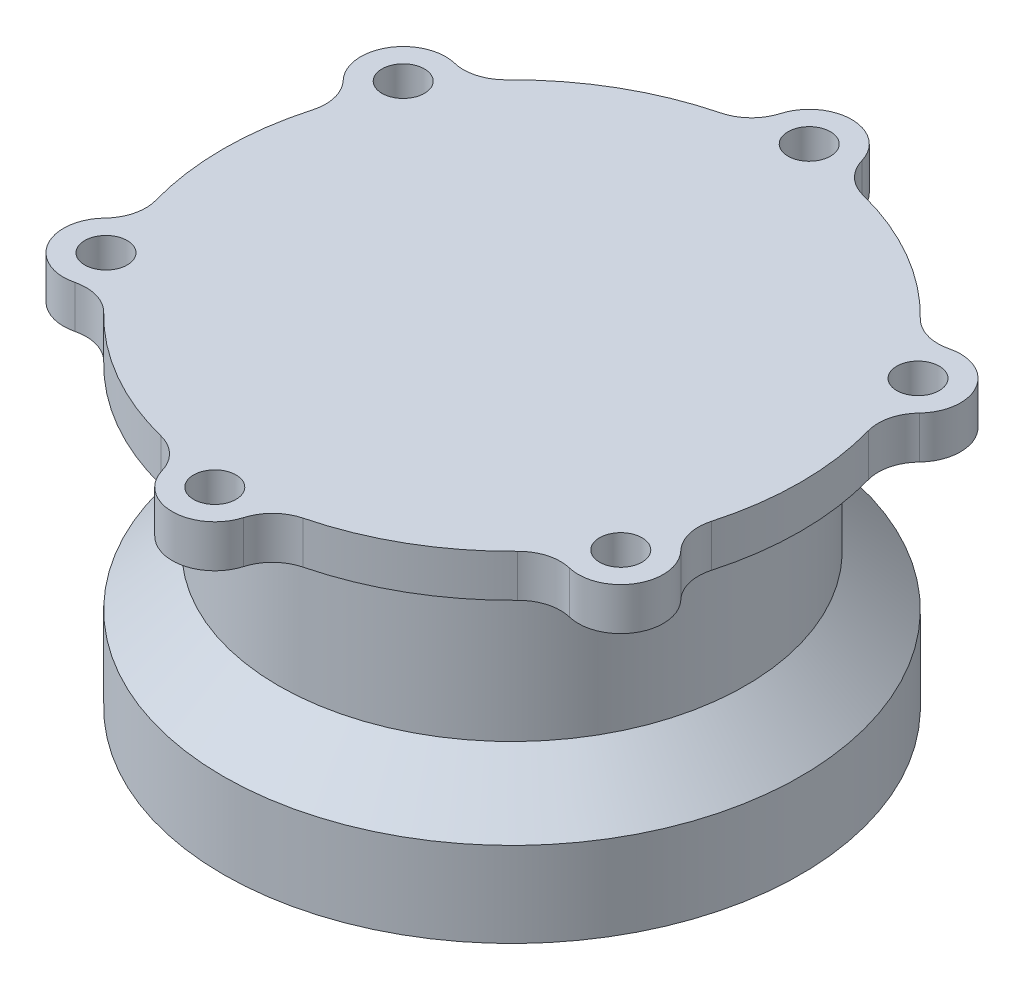
SolidWorks part; units mm, degrees
ref_plane "Front Plane" through (0, 0, 0) normal (0, 0, 1) x (1, 0, 0)
ref_plane "Top Plane" through (0, 0, 0) normal (0, 1, 0) x (1, 0, 0)
ref_plane "Right Plane" through (0, 0, 0) normal (1, 0, 0) x (0, 0, -1)
sketch "Sketch3" plane through (0, 0, 0) normal (0, 0, 1) x (1, 0, 0)
  line L0 (0, 0) -> (-34, 0)
  line L1 (-34, 0) -> (-34, 10)
  line L2 (-34, 10) -> (-27.5, 16)
  line L3 (-27.5, 16) -> (-27.5, 35)
  line L4 (-27.5, 35) -> (0, 35)
  line L5 (0, 35) -> (0, 0)
  line L6 (0, 67.2766) -> (0, -30.9617) construction
  dimension "D1" = 68
  dimension "D2" = 10
  dimension "D3" = 6
  dimension "D4" = 55
  dimension "D5" = 35
revolve "Revolve1" add sketch "Sketch3" angle 360 about L6
sketch "Sketch2" plane through (0, 35, 0) normal (0, 1, 0) x (1, 0, 0)
  line L0 (0, 35) -> (-30.3109, 17.5) construction
  line L1 (0, 35) -> (30.3109, 17.5) construction
  circle A0 centre (0, 0) radius 35
  circle A1 centre (0, 35) radius 2.5
  circle A2 centre (30.3109, 17.5) radius 2.5
  circle A3 centre (30.3109, -17.5) radius 2.5
  circle A4 centre (0, -35) radius 2.5
  circle A5 centre (-30.3109, -17.5) radius 2.5
  circle A6 centre (-30.3109, 17.5) radius 2.5
  circle A7 centre (0, 35) radius 5
  circle A8 centre (30.3109, 17.5) radius 5
  circle A9 centre (30.3109, -17.5) radius 5
  circle A10 centre (0, -35) radius 5
  circle A11 centre (-30.3109, -17.5) radius 5
  circle A12 centre (-30.3109, 17.5) radius 5
  circle A13 centre (0, 0) radius 34 construction
  circle A14 centre (0, 0) radius 34
  point P17 (0, 0)
  circle M17 centre (0, 0) radius 27.5
  dimension "D1" = 70
  dimension "D2" = 5
  dimension "D4" = 10
  dimension "D3" = 6
extrude "Boss-Extrude2" add sketch "Sketch2" along normal blind 5 contours A10 A14 A9 A8 A7 A12 A11 M17 | M17 | A7 A14 A1 | A14 A1 A0 A7 | A14 A7 A0 A1 | A0 A7 A1 | A0 A8 A2 | A14 A2 A0 A8 | A14 A8 A0 A2 | A8 A14 A2 | A14 A3 A0 A9 | A9 A14 A3 | A14 A9 A0 A3 | A14 A10 A0 A4 | A14 A4 A0 A10 | A4 A14 A10 | A14 A11 A0 A5 | A14 A5 A0 A11 | A11 A14 A5 | A14 A12 A0 A6 | A12 A14 A6 | A14 A6 A0 A12 | A0 A12 A6 | A0 A11 A5 | A0 A10 A4 | A0 A9 A3
fillet "Fillet1" radius 5 12 edges at (-26.7398, 37.5, 20.9996) (-31.5561, 37.5, 12.6575) (-31.5561, 37.5, -12.6575) (-26.7398, 37.5, -20.9996) (-4.8163, 37.5, -33.6571) (4.8163, 37.5, -33.6571) (26.7398, 37.5, -20.9996) (31.5561, 37.5, -12.6575) (31.5561, 37.5, 12.6575) (26.7398, 37.5, 20.9996) (4.8163, 37.5, 33.6571) (-4.8163, 37.5, 33.6571)
